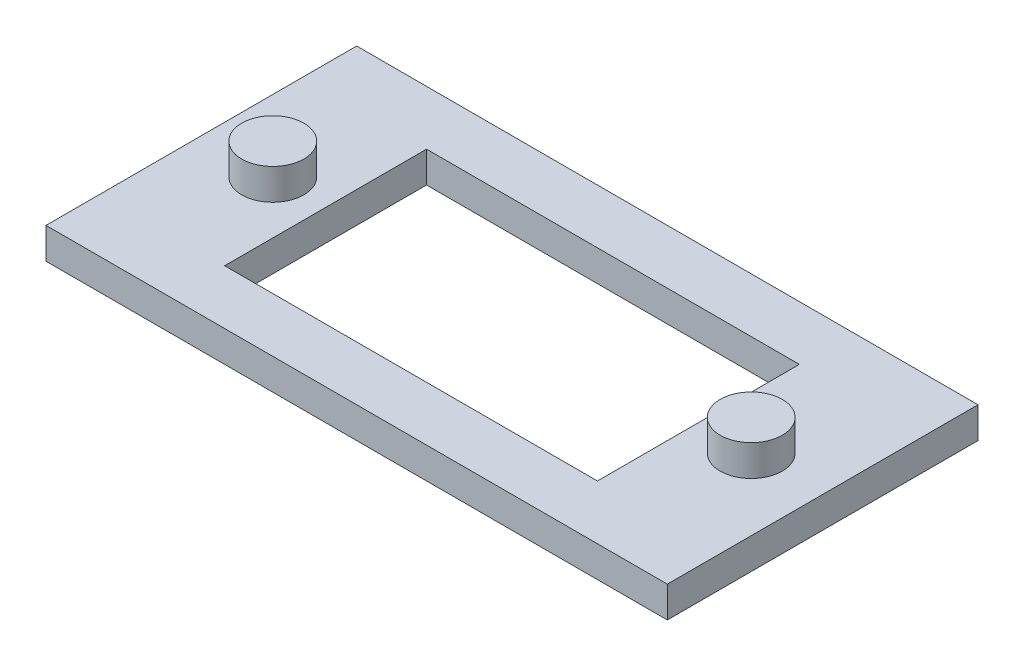
SolidWorks part; units mm, degrees
ref_plane "Front Plane" through (0, 0, 0) normal (0, 0, 1) x (1, 0, 0)
ref_plane "Top Plane" through (0, 0, 0) normal (0, 1, 0) x (1, 0, 0)
ref_plane "Right Plane" through (0, 0, 0) normal (1, 0, 0) x (0, 0, -1)
sketch "Sketch1" plane through (0, 0, 0) normal (0, 1, 0) x (1, 0, 0)
  line L1 (-10, -5) -> (10, -5)
  line L2 (-10, -5) -> (-10, 5)
  line L3 (-10, 5) -> (10, 5)
  line L4 (10, -5) -> (10, 5)
  line L5 (-10, -5) -> (10, 5) construction
  line L6 (-10, 5) -> (10, -5) construction
  point P0 (0, 0)
  dimension "D1" = 10
  dimension "D2" = 20
extrude "Boss-Extrude1" add sketch "Sketch1" along normal blind 1
sketch "Sketch2" plane through (0, 1, 0) normal (0, 1, 0) x (1, 0, 0)
  line L1 (-6, -3.25) -> (6, -3.25)
  line L2 (-6, -3.25) -> (-6, 3.25)
  line L3 (-6, 3.25) -> (6, 3.25)
  line L4 (6, -3.25) -> (6, 3.25)
  line L5 (-6, -3.25) -> (6, 3.25) construction
  line L6 (-6, 3.25) -> (6, -3.25) construction
  point P0 (0, 0)
  dimension "D1" = 6.5
  dimension "D2" = 12
extrude "Cut-Extrude1" cut sketch "Sketch2" against normal blind 4
sketch "Sketch3" plane through (0, 1, 0) normal (0, 1, 0) x (1, 0, 0)
  line L0 (0, 5) -> (0, -4.9881) construction
  line L1 (10, 5) -> (-10, 5) construction
  line L2 (-6, 3.25) -> (-6, -3.25) construction
  circle A0 centre (-7.7, 0) radius 1
  circle A1 centre (7.7, 0) radius 1
  dimension "D1" = 2
  dimension "D2" = 1.7
extrude "Boss-Extrude2" add sketch "Sketch3" along normal blind 1
